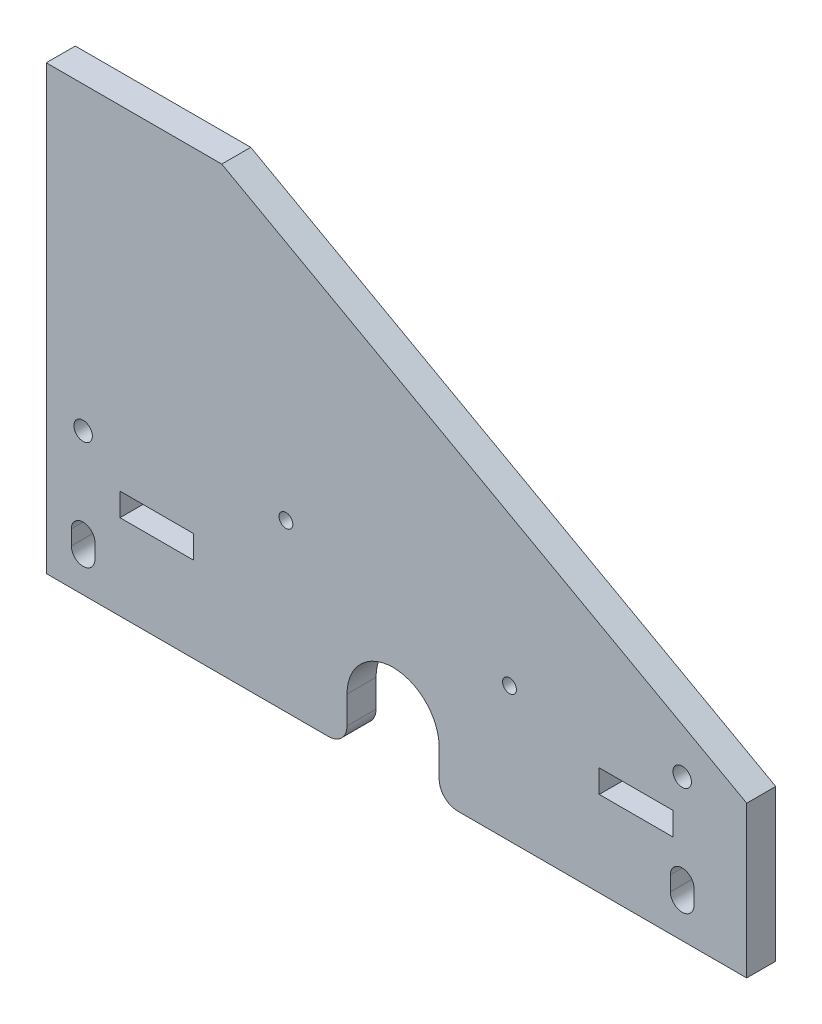
SolidWorks part; units mm, degrees
ref_plane "Front Plane" through (0, 0, 0) normal (0, 0, 1) x (1, 0, 0)
ref_plane "Top Plane" through (0, 0, 0) normal (0, 1, 0) x (1, 0, 0)
ref_plane "Right Plane" through (0, 0, 0) normal (1, 0, 0) x (0, 0, -1)
sketch "Sketch1" plane through (0, 0, 0) normal (0, 0, 1) x (1, 0, 0)
  line L0 (-141.9266, 127.8181) -> (38.9214, 27.5724)
  line L1 (-202.3786, 127.8181) -> (-141.9266, 127.8181)
  line L2 (-202.3786, 127.8181) -> (-202.3786, -24.5819)
  line L3 (-202.3786, -24.5819) -> (38.9214, -24.5819)
  line L4 (38.9214, 27.5724) -> (38.9214, -24.5819)
  line L5 (-202.3786, 127.8181) -> (38.9214, -24.5819) construction
  line L6 (-202.3786, -24.5819) -> (-112.8718, -13.71) construction
  point P0 (0, 0)
  dimension "D1" = 60.452
  dimension "D2" = 241.3
  dimension "D3" = 152.4
  dimension "D4" = 151
extrude "Boss-Extrude1" add sketch "Sketch1" along normal blind 10
sketch "Sketch3" plane through (0, 0, 10) normal (0, 0, 1) x (1, 0, 0)
  line L1 (-176.9786, 4.7881) -> (-151.5786, 4.7881)
  line L2 (-176.9786, 4.7881) -> (-176.9786, 12.7256)
  line L3 (-176.9786, 12.7256) -> (-151.5786, 12.7256)
  line L4 (-151.5786, 4.7881) -> (-151.5786, 12.7256)
  dimension "D1" = 25.4
  dimension "D2" = 29.37
  dimension "D3" = 25.4
  dimension "D4" = 7.9375
extrude "Cut-Extrude1" cut sketch "Sketch3" against normal up to next
sketch "Sketch4" plane through (0, 0, 10) normal (0, 0, 1) x (1, 0, 0)
  line L0 (-185.6146, -6.9289) -> (-185.6146, -12.0089)
  line L2 (-193.7426, -12.0089) -> (-193.7426, -6.9289)
  arc A0 (-193.7426, -12.0089) -> (-185.6146, -12.0089) centre (-189.6786, -12.0089) ccw
  arc A1 (-185.6146, -6.9289) -> (-193.7426, -6.9289) centre (-189.6786, -6.9289) ccw
  dimension "D1" = 4.064
  dimension "D2" = 4.064
  dimension "D3" = 5.08
  dimension "D4" = 12.573
  dimension "D5" = 12.7
  dimension "D6" = 12.7
extrude "Cut-Extrude2" cut sketch "Sketch4" against normal up to next
sketch "Sketch6" plane through (0, 0, 10) normal (0, 0, 1) x (1, 0, 0)
  line L0 (-202.3786, 127.8181) -> (-202.3786, -24.5819) construction
  circle A0 centre (-189.6786, 24.3588) radius 3.175
  dimension "D1" = 6.35
  dimension "D2" = 12.7
  dimension "D3" = 48.9407
extrude "Cut-Extrude3" cut sketch "Sketch6" against normal blind 10
sketch "Sketch7" plane through (0, 0, 10) normal (0, 0, 1) x (1, 0, 0)
  line L0 (-202.3786, -24.5819) -> (38.9214, -24.5819) construction
  circle A0 centre (-119.8286, 32.5681) radius 2.3813
  dimension "D1" = 4.7625
  dimension "D2" = 82.55
  dimension "D3" = 57.15
extrude "Cut-Extrude4" cut sketch "Sketch7" against normal blind 10
sketch "Sketch8" plane through (0, 0, 10) normal (0, 0, 1) x (1, 0, 0)
  line L0 (-202.3786, -24.5819) -> (38.9214, -24.5819) construction
  line L1 (-202.3786, 127.8181) -> (-202.3786, -24.5819) construction
  circle A0 centre (-42.793, 21.7731) radius 2.3813
  dimension "D1" = 4.7625
  dimension "D2" = 46.355
  dimension "D3" = 159.5857
extrude "Cut-Extrude5" cut sketch "Sketch8" against normal blind 10
sketch "Sketch9" plane through (0, 0, 10) normal (0, 0, 1) x (1, 0, 0)
  line L0 (38.9214, -24.5819) -> (38.9214, 27.5724) construction
  line L1 (13.5214, 12.7256) -> (-11.8786, 12.7256)
  line L2 (13.5214, 12.7256) -> (13.5214, 4.7881)
  line L3 (13.5214, 4.7881) -> (-11.8786, 4.7881)
  line L4 (-11.8786, 12.7256) -> (-11.8786, 4.7881)
  line L5 (-202.3786, -24.5819) -> (38.9214, -24.5819) construction
  dimension "D1" = 25.4
  dimension "D2" = 29.37
  dimension "D3" = 7.9375
  dimension "D4" = 25.4
extrude "Cut-Extrude6" cut sketch "Sketch9" against normal blind 10
pattern_linear "LPattern1" count 2 spacing 206.375 along (1, 0, 0) of "Cut-Extrude2"
pattern_linear "LPattern4" count 2 spacing 206.375 along (1, 0, 0) of "Cut-Extrude3"
sketch "Sketch11" plane through (0, 0, 10) normal (0, 0, 1) x (1, 0, 0)
  line L0 (-98.7695, -8.7069) -> (-98.7695, -18.2319)
  line L1 (-67.0195, -8.7069) -> (-67.0195, -18.2319)
  line L2 (-202.3786, -24.5819) -> (38.9214, -24.5819) construction
  line L3 (-105.1195, -24.5819) -> (-60.6695, -24.5819)
  line L4 (-202.3786, 127.8181) -> (-202.3786, -24.5819) construction
  arc A0 (-67.0195, -8.7069) -> (-98.7695, -8.7069) centre (-82.8945, -8.7069) ccw
  arc A1 (-105.1195, -24.5819) -> (-98.7695, -18.2319) centre (-105.1195, -18.2319) ccw
  arc A2 (-67.0195, -18.2319) -> (-60.6695, -24.5819) centre (-60.6695, -18.2319) ccw
  dimension "D2" = 15.875
  dimension "D3" = 6.35
  dimension "D4" = 6.35
  dimension "D1" = 15.875
  dimension "D5" = 119.4841
extrude "Cut-Extrude7" cut sketch "Sketch11" against normal blind 10
